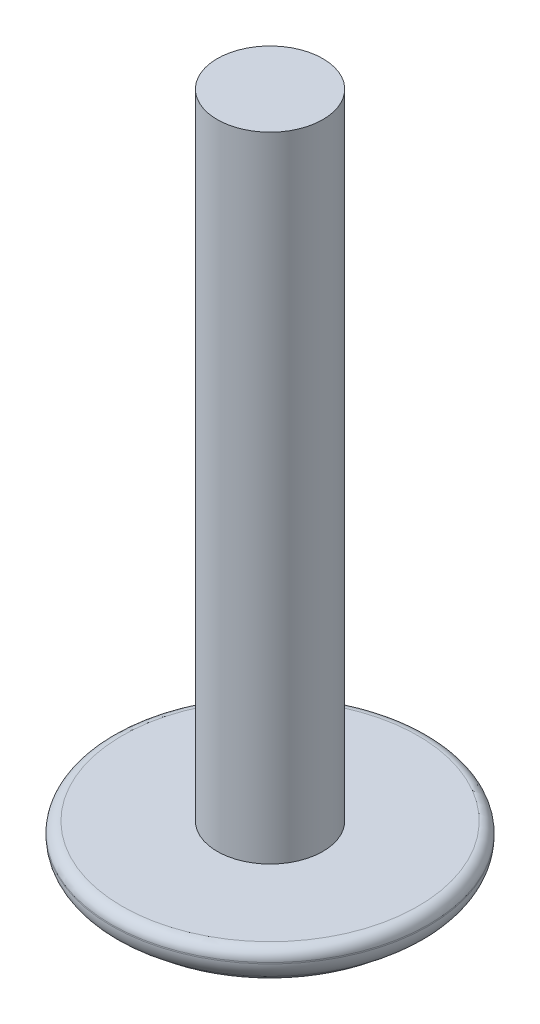
SolidWorks part; units mm, degrees
material "AISI 1045 Steel, cold drawn"
ref_plane "Front Plane" through (0, 0, 0) normal (1, 0, 0) x (0, 1, 0)
ref_plane "Top Plane" through (0, 0, 0) normal (0, 0, 1) x (0, 1, 0)
ref_plane "Right Plane" through (0, 0, 0) normal (0, 1, 0) x (-1, 0, 0)
sketch "Sketch1" plane through (0, 0, 0) normal (1, 0, 0) x (0, 1, 0)
  line L0 (0, 12.6738) -> (0, -14.1332) construction
  line L1 (-13.8486, 0) -> (25.4018, 0) construction
  line L2 (-1, 7.5) -> (0, 7.5)
  line L3 (0, 7.5) -> (0, 0)
  line L4 (-4, 0) -> (0, 0)
  line L5 (0, 2.5) -> (30, 2.5)
  line L6 (30, 2.5) -> (30, 0)
  line L7 (0, 0) -> (30, 0)
  arc A3 (-1, 7.5) -> (-4, 0) centre (6.875, 0) ccw
  dimension "D1" = 1
  dimension "D2" = 7.5
  dimension "D3" = 4
  dimension "D5" = 30
  dimension "D6" = 5
revolve "Revolve1" add sketch "Sketch1" angle 360 about L1
fillet "Fillet1" radius 0.5 1 edges at (0, 0, -7.5)
fillet "Fillet2" radius 1 1 edges at (0, -1, -7.5)
